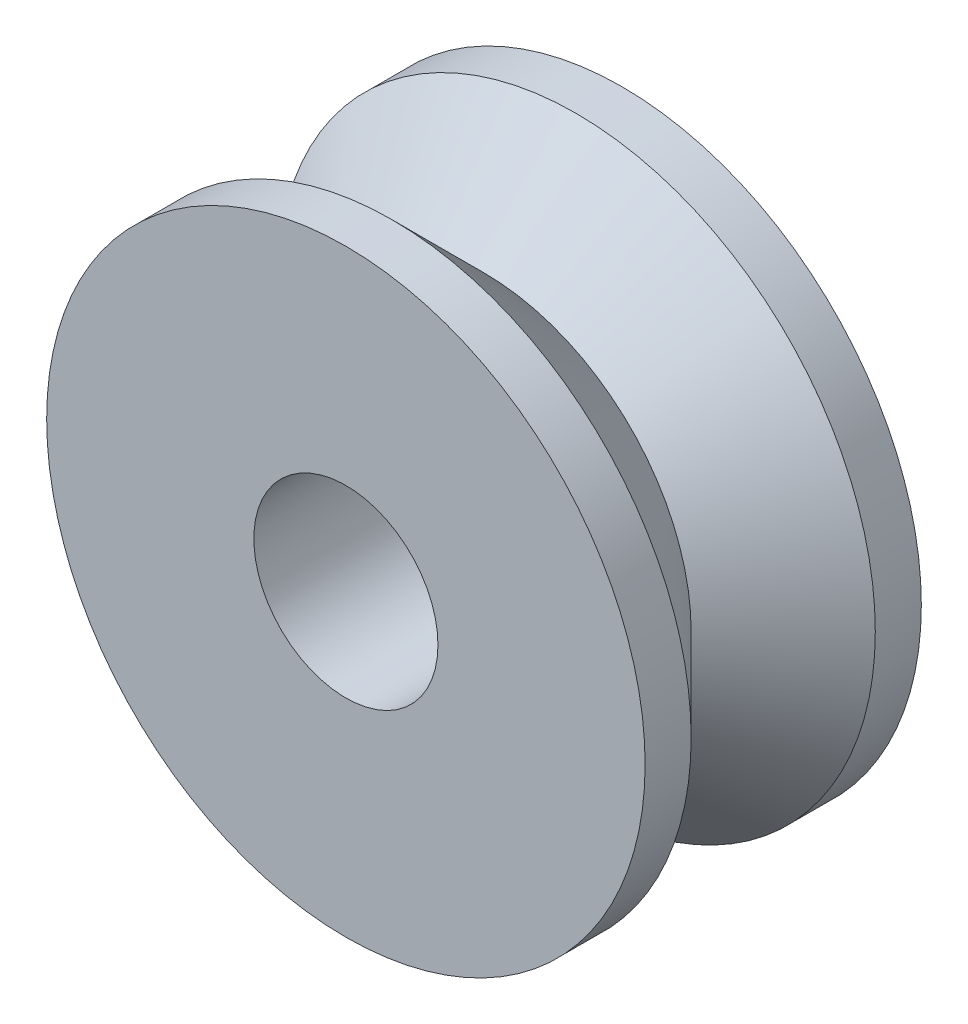
SolidWorks part; units mm, degrees
ref_plane "Front Plane" through (0, 0, 0) normal (0, 0, 1) x (1, 0, 0)
ref_plane "Top Plane" through (0, 0, 0) normal (0, 1, 0) x (1, 0, 0)
ref_plane "Right Plane" through (0, 0, 0) normal (1, 0, 0) x (0, 0, -1)
ref_axis "Axis1" through (0, 0, 55) along (0, 0, -1)
sketch "Sketch1" plane through (0, 0, 0) normal (1, 0, 0) x (0, 0, -1)
  line L0 (0, 0) -> (0, 6.5)
  line L1 (0, 6.5) -> (-1, 6.5)
  line L2 (-6, 6.5) -> (-6, 0)
  line L3 (-55, 0) -> (55, 0) construction
  line L4 (-6, 0) -> (0, 0)
  line L5 (-1, 6.5) -> (-1, 0) construction
  line L6 (-5, 6.5) -> (-5, 0) construction
  line L8 (-5, 6.5) -> (-6, 6.5)
  line L9 (-5, 6.5) -> (-3, 4.5)
  line L10 (-3, 4.5) -> (-1, 6.5)
revolve "Revolve1" add sketch "Sketch1" angle 360 about axis through (0, 0, 55) along (0, 0, -1)
hole_wizard "Ø4.0 (4) Diameter Hole1" positions "Sketch3" profile "Sketch2" hole size "Ø4.0" standard "ANSI Metric" end condition through all
sketch "Sketch3" plane through (0, 0, 6) normal (0, 0, 1) x (1, 0, 0)
  point P0 (0, 0)
sketch "Sketch2" plane through (0, 0, 6) normal (1, 0, 0) x (0, -1, 0)
  line L0 (0, 0) -> (0, 6)
  line L1 (0, 6) -> (2, 6)
  line L2 (2, 6) -> (2, 0)
  line L5 (2, 0) -> (0, 0)
  line L11 (0, -6.35) -> (0, 107.95) construction
  dimension "Thru Hole Dia." = 4
  dimension "Thru Hole Depth" = 6
